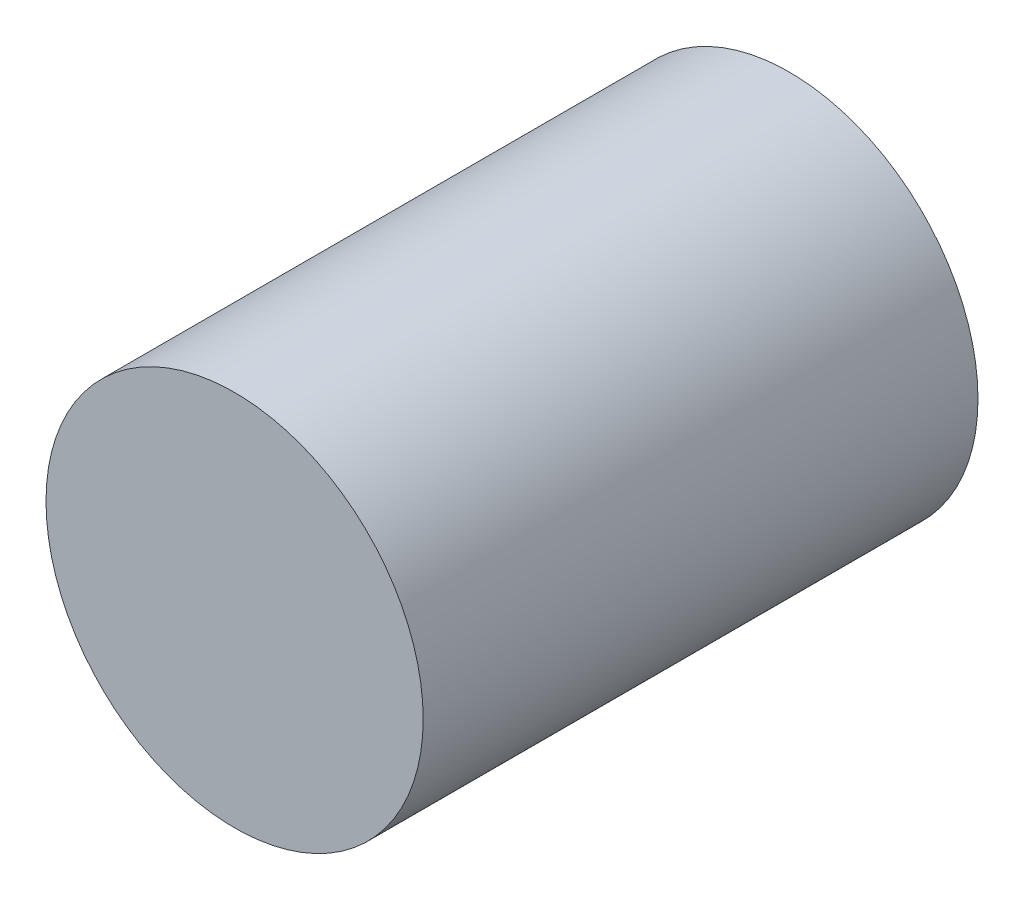
SolidWorks part; units mm, degrees
ref_plane "Ön Düzlem" through (0, 0, 0) normal (0, 0, 1) x (1, 0, 0)
ref_plane "Üst Düzlem" through (0, 0, 0) normal (0, 1, 0) x (1, 0, 0)
ref_plane "Sağ Düzlem" through (0, 0, 0) normal (1, 0, 0) x (0, 0, -1)
sketch "Çizim1" plane through (0, 0, 0) normal (0, 0, 1) x (1, 0, 0)
  circle A0 centre (0, 0) radius 27.5
  dimension "D1" = 55
extrude "Yükseklik-Ekstrüzyon1" add sketch "Çizim1" along normal blind 80.9
